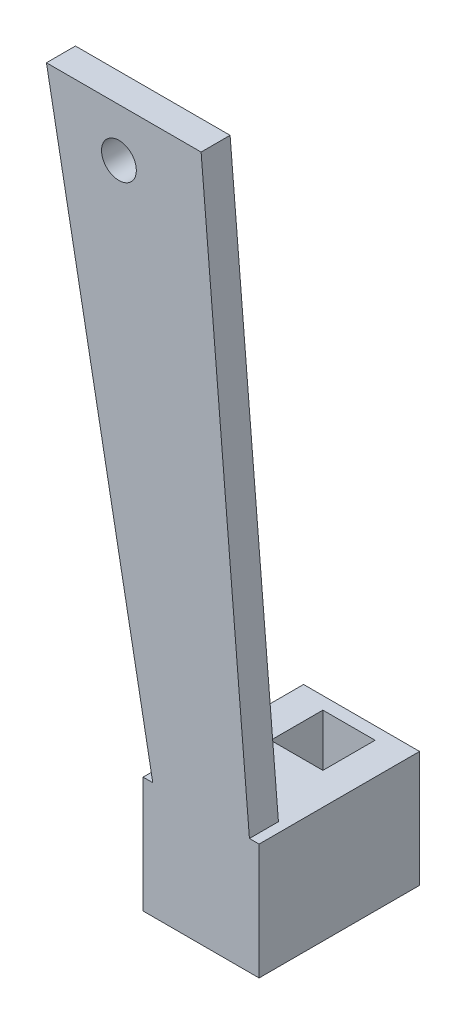
SolidWorks part; units mm, degrees
material "Plain Carbon Steel"
ref_plane "Front Plane" through (0, 0, 0) normal (0, 0, 1) x (1, 0, 0)
ref_plane "Top Plane" through (0, 0, 0) normal (0, 1, 0) x (1, 0, 0)
ref_plane "Right Plane" through (0, 0, 0) normal (1, 0, 0) x (0, 0, -1)
sketch "Sketch1" plane through (0, 0, 0) normal (0, 0, 1) x (1, 0, 0)
  line L0 (-6, -6) -> (6, -6)
  line L1 (6, -6) -> (6, 6)
  line L2 (6, 6) -> (-6, 6)
  line L3 (-6, 6) -> (-6, -6)
  dimension "D1" = 12
  dimension "D2" = 12
  dimension "D3" = 6
  dimension "D4" = 6
extrude "Boss-Extrude1" add sketch "Sketch1" along normal blind 16.6 from offset 4
sketch "Sketch2" plane through (0, 0, 0) normal (0, 1, 0) x (1, 0, 0)
  line L0 (-2.7, -2.7) -> (2.7, -2.7)
  line L1 (2.7, -2.7) -> (2.7, 2.7)
  line L2 (2.7, 2.7) -> (-2.7, 2.7)
  line L3 (-2.7, 2.7) -> (-2.7, -2.7)
  dimension "D1" = 5.4
  dimension "D2" = 5.4
  dimension "D3" = 2.7
  dimension "D4" = 2.7
extrude "Cut-Extrude1" cut sketch "Sketch2" against normal mid plane 24
sketch "Sketch3" plane through (0, 0, 0) normal (0, 0, 1) x (1, 0, 0)
  line L0 (-5, 6) -> (5, 6)
  line L1 (5, 6) -> (0, 65)
  line L2 (0, 65) -> (-16, 65)
  line L3 (-16, 65) -> (-5, 6)
  dimension "D1" = 5
  dimension "D2" = 6
  dimension "D3" = 10
  dimension "D4" = 5
  dimension "D5" = 59
  dimension "D6" = 16
extrude "Boss-Extrude2" add sketch "Sketch3" along normal blind 3 from offset 9.6
sketch "Sketch4" plane through (0, 0, 0) normal (0, 0, 1) x (1, 0, 0)
  circle A0 centre (-8.5, 60) radius 1.8
  dimension "D3" = 3.6
  dimension "D1" = 8.5
  dimension "D2" = 60
extrude "Cut-Extrude2" cut sketch "Sketch4" against normal mid plane 50.4
